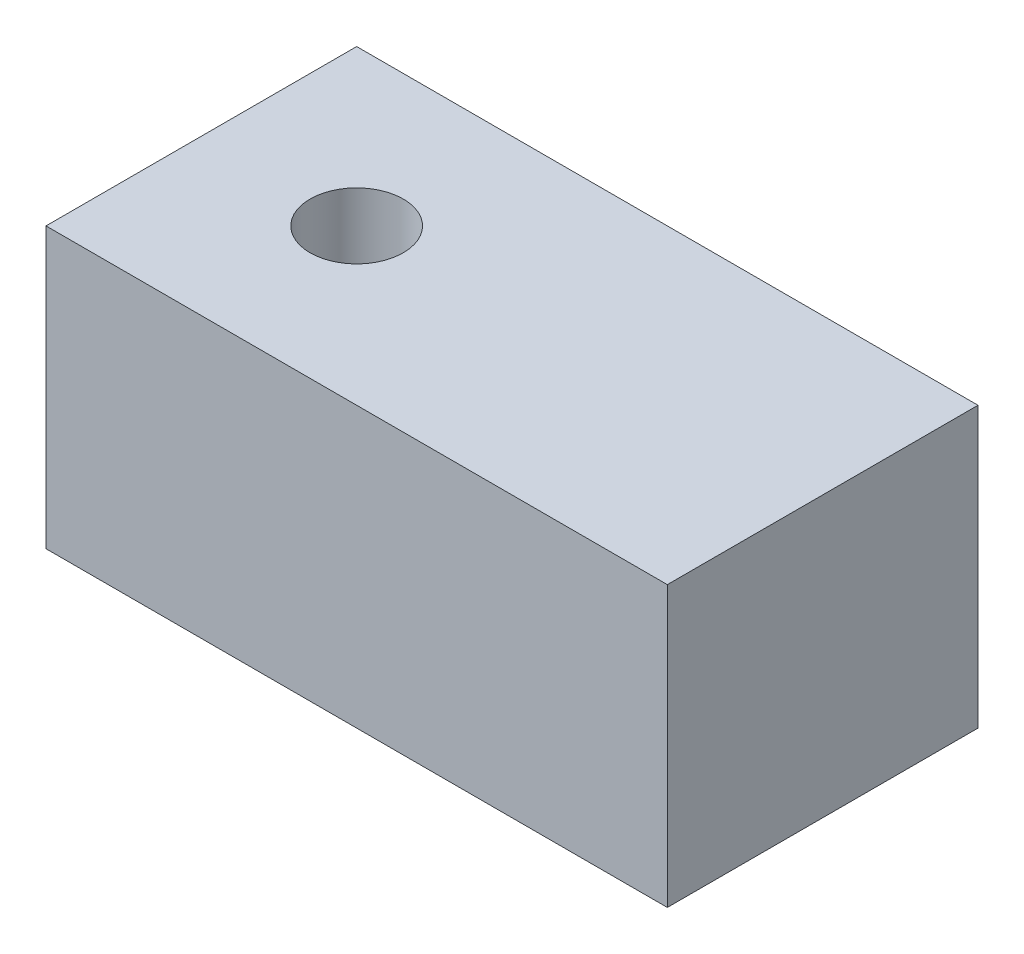
SolidWorks part; units mm, degrees
ref_plane "前视基准面" through (0, 0, 0) normal (0, 0, 1) x (1, 0, 0)
ref_plane "上视基准面" through (0, 0, 0) normal (0, 1, 0) x (1, 0, 0)
ref_plane "右视基准面" through (0, 0, 0) normal (1, 0, 0) x (0, 0, -1)
other "Configuration Table"
sketch "草图1" plane through (0, 0, 0) normal (0, 1, 0) x (1, 0, 0)
  line L1 (-10, 5) -> (10, 5)
  line L2 (-10, 5) -> (-10, -5)
  line L3 (-10, -5) -> (10, -5)
  line L4 (10, 5) -> (10, -5)
  line L5 (-10, 5) -> (10, -5) construction
  line L6 (-10, -5) -> (10, 5) construction
  point P0 (0, 0)
  dimension "D1" = 20
  dimension "D2" = 10
extrude "凸台-拉伸1" add sketch "草图1" along normal blind 9
sketch "草图2" plane through (0, 9, 0) normal (0, 1, 0) x (1, 0, 0)
  line L0 (-10, 0) -> (17.4571, 0) construction
  line L1 (-10, 5) -> (-10, -5) construction
  circle A0 centre (-5, 0) radius 1.5
  dimension "D1" = 3
  dimension "D2" = 5
extrude "切除-拉伸2" cut sketch "草图2" against normal through all
